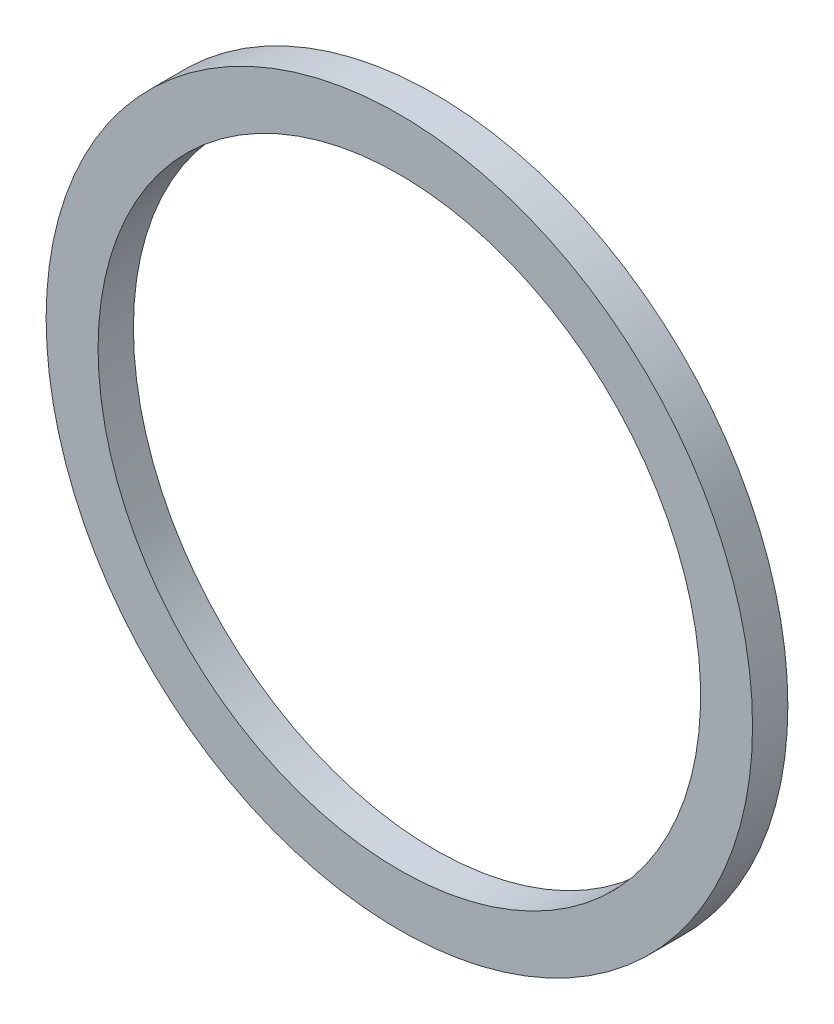
SolidWorks part; units mm, degrees
ref_plane "Спереди" through (0, 0, 0) normal (0, 0, 1) x (1, 0, 0)
ref_plane "Сверху" through (0, 0, 0) normal (0, 1, 0) x (1, 0, 0)
ref_plane "Справа" through (0, 0, 0) normal (1, 0, 0) x (0, 0, -1)
sketch "Эскиз1" plane through (0, 0, 0) normal (0, 0, 1) x (1, 0, 0)
  circle A0 centre (0, 0) radius 34
  circle A1 centre (0, 0) radius 29
  dimension "D1" = 68
  dimension "D2" = 58
extrude "Бобышка-Вытянуть1" add sketch "Эскиз1" along normal blind 3.4
